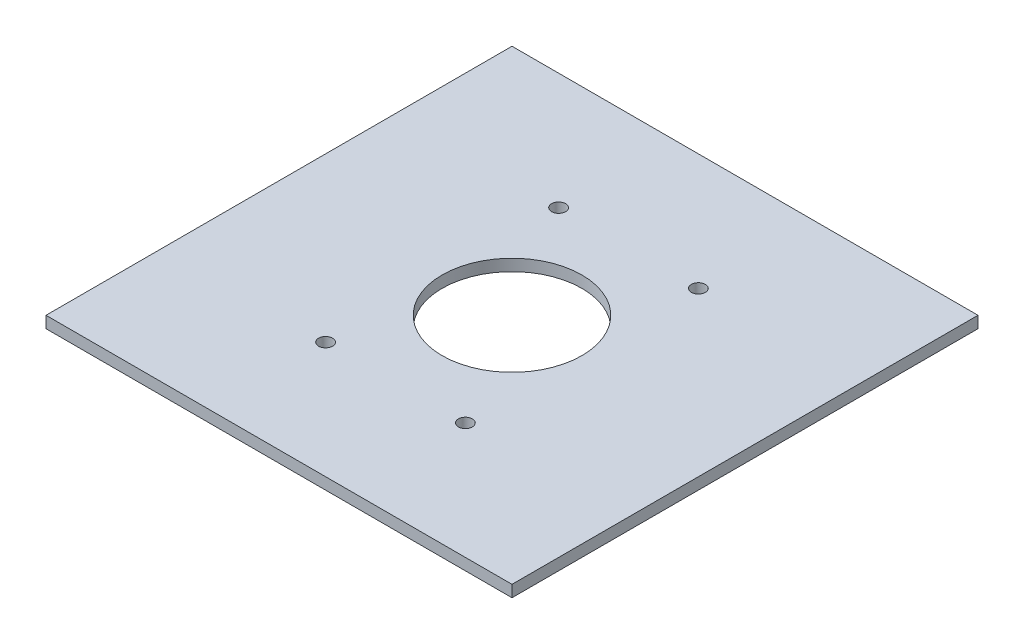
SolidWorks part; units mm, degrees
ref_plane "Front Plane" through (0, 0, 0) normal (0, 0, 1) x (1, 0, 0)
ref_plane "Top Plane" through (0, 0, 0) normal (0, 1, 0) x (1, 0, 0)
ref_plane "Right Plane" through (0, 0, 0) normal (1, 0, 0) x (0, 0, -1)
sketch "Sketch1" plane through (0, 0, 0) normal (0, 1, 0) x (1, 0, 0)
  line L1 (-63.5, -63.5) -> (63.5, -63.5)
  line L2 (-63.5, -63.5) -> (-63.5, 63.5)
  line L3 (-63.5, 63.5) -> (63.5, 63.5)
  line L4 (63.5, -63.5) -> (63.5, 63.5)
  line L5 (-63.5, -63.5) -> (63.5, 63.5) construction
  line L6 (-63.5, 63.5) -> (63.5, -63.5) construction
  point P0 (0, 0)
  dimension "D1" = 127
  dimension "D2" = 127
extrude "Boss-Extrude1" add sketch "Sketch1" along normal blind 3.175
sketch "Sketch2" plane through (0, 0, 0) normal (0, 1, 0) x (1, 0, 0)
  line L1 (19.05, 31.75) -> (-19.05, 31.75) construction
  line L2 (19.05, 31.75) -> (19.05, -31.75) construction
  line L3 (19.05, -31.75) -> (-19.05, -31.75) construction
  line L4 (-19.05, 31.75) -> (-19.05, -31.75) construction
  line L5 (19.05, 31.75) -> (-19.05, -31.75) construction
  line L6 (19.05, -31.75) -> (-19.05, 31.75) construction
  circle A0 centre (0, 0) radius 19.05
  circle A1 centre (19.05, 31.75) radius 1.905
  circle A2 centre (-19.05, 31.75) radius 1.905
  circle A3 centre (-19.05, -31.75) radius 1.905
  circle A4 centre (19.05, -31.75) radius 1.905
  point P8 (0, 31.75)
  dimension "D1" = 38.1
  dimension "D4" = 3.81
  dimension "D2" = 38.1
  dimension "D3" = 63.5
extrude "Cut-Extrude1" cut sketch "Sketch2" along normal through all
